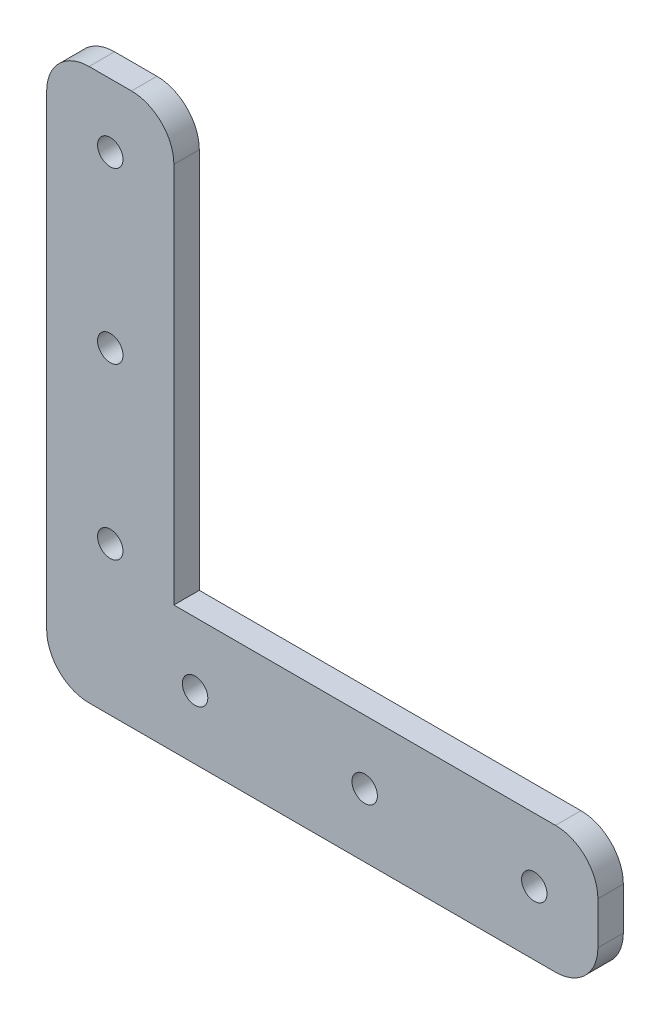
SolidWorks part; units mm, degrees
material "Thornel Mat VMA"
ref_plane "前视基准面" through (0, 0, 0) normal (0, 0, 1) x (1, 0, 0)
ref_plane "上视基准面" through (0, 0, 0) normal (0, 1, 0) x (1, 0, 0)
ref_plane "右视基准面" through (0, 0, 0) normal (1, 0, 0) x (0, 0, -1)
sketch "草图1" plane through (0, 0, 0) normal (0, 0, 1) x (1, 0, 0)
  line L0 (0, 0) -> (0, 65)
  line L1 (0, 65) -> (15, 65)
  line L4 (65, 15) -> (65, 0)
  line L5 (65, 0) -> (0, 0)
  line L6 (7.5, 65) -> (7.5, 7.5) construction
  line L7 (7.5, 7.5) -> (65, 7.5) construction
  line L10 (15, 65) -> (15, 15)
  line L11 (15, 15) -> (65, 15)
  line L13 (0, 0) -> (7.5, 7.5) construction
  circle A0 centre (7.5, 57.5) radius 1.5
  circle A1 centre (7.5, 37.5) radius 1.5
  circle A2 centre (7.5, 17.5) radius 1.5
  circle A3 centre (57.5, 7.5) radius 1.5
  circle A4 centre (37.5, 7.5) radius 1.5
  circle A5 centre (17.5, 7.5) radius 1.5
  dimension "D14" = 3
  dimension "D16" = 20
  dimension "D17" = 20
  dimension "D1" = 15
  dimension "D2" = 7.5
  dimension "D3" = 7.5
  dimension "D4" = 15
  dimension "D6" = 65
  dimension "D7" = 65
  dimension "D15" = 10
extrude "凸台-拉伸1" add sketch "草图1" along normal blind 3
fillet "圆角1" radius 5 5 edges at (0, 0, 1.5) (65, 0, 1.5) (0, 65, 1.5) (65, 15, 1.5) (15, 65, 1.5)
